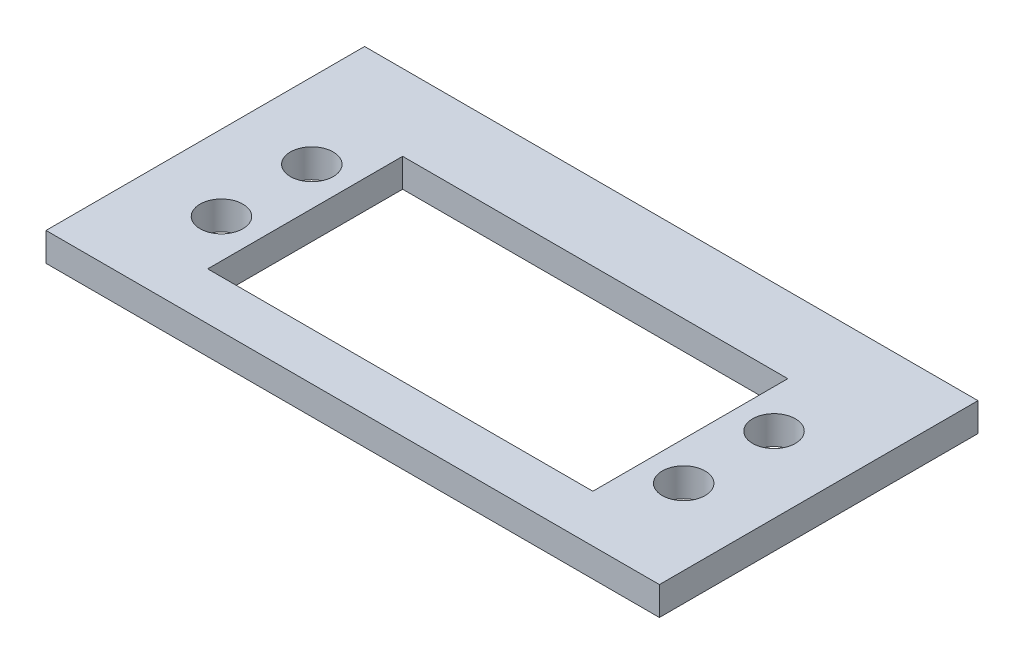
SolidWorks part; units mm, degrees
ref_plane "Front Plane" through (0, 0, 0) normal (0, 0, 1) x (1, 0, 0)
ref_plane "Top Plane" through (0, 0, 0) normal (0, 1, 0) x (1, 0, 0)
ref_plane "Right Plane" through (0, 0, 0) normal (1, 0, 0) x (0, 0, -1)
sketch "Sketch2" plane through (0, 0, 0) normal (0, 1, 0) x (1, 0, 0)
  line L0 (5, 41.9042) -> (5, -23.1473) construction
  line L1 (0, 0) -> (64.5, 0)
  line L2 (0, 0) -> (0, 33.5)
  line L3 (0, 33.5) -> (64.5, 33.5)
  line L4 (64.5, 0) -> (64.5, 33.5)
  line L5 (59.5, 41.9042) -> (59.5, -20.3718) construction
  line L6 (12, 41.9042) -> (12, -23.4943) construction
  line L7 (52.5, 43.292) -> (52.5, -24.882) construction
  line L8 (-9.7643, 25.5) -> (78.3722, 25.5) construction
  line L9 (78.3722, 5) -> (-9.7643, 5) construction
  line L10 (-9.7643, 15.25) -> (81.891, 15.25) construction
  line L11 (81.891, 20) -> (-11.775, 20) construction
  line L12 (-11.775, 10.5) -> (80.8856, 10.5) construction
  line L13 (56.55, 43.292) -> (56.55, -20.917) construction
  line L14 (12, 5) -> (52.5, 5)
  line L15 (12, 5) -> (12, 25.5)
  line L16 (12, 25.5) -> (52.5, 25.5)
  line L17 (52.5, 5) -> (52.5, 25.5)
  line L18 (7.95, 41.9042) -> (7.95, -23.8191) construction
  circle A0 centre (7.95, 20) radius 2.25
  circle A1 centre (7.95, 10.5) radius 2.25
  circle A2 centre (56.55, 20) radius 2.25
  circle A3 centre (56.55, 10.5) radius 2.25
  dimension "D14" = 4.5
  dimension "D15" = 4.5
  dimension "D16" = 4.5
  dimension "D17" = 4.5
  dimension "D1" = 5
  dimension "D2" = 7
  dimension "D3" = 5
  dimension "D4" = 7
  dimension "D5" = 40.5
  dimension "D6" = 15.25
  dimension "D7" = 8
  dimension "D8" = 5
  dimension "D9" = 20.5
  dimension "D10" = 4.75
  dimension "D11" = 4.75
  dimension "D12" = 4.05
  dimension "D13" = 4.05
  dimension "D18" = 9.5
extrude "Boss-Extrude1" add sketch "Sketch2" along normal blind 3
